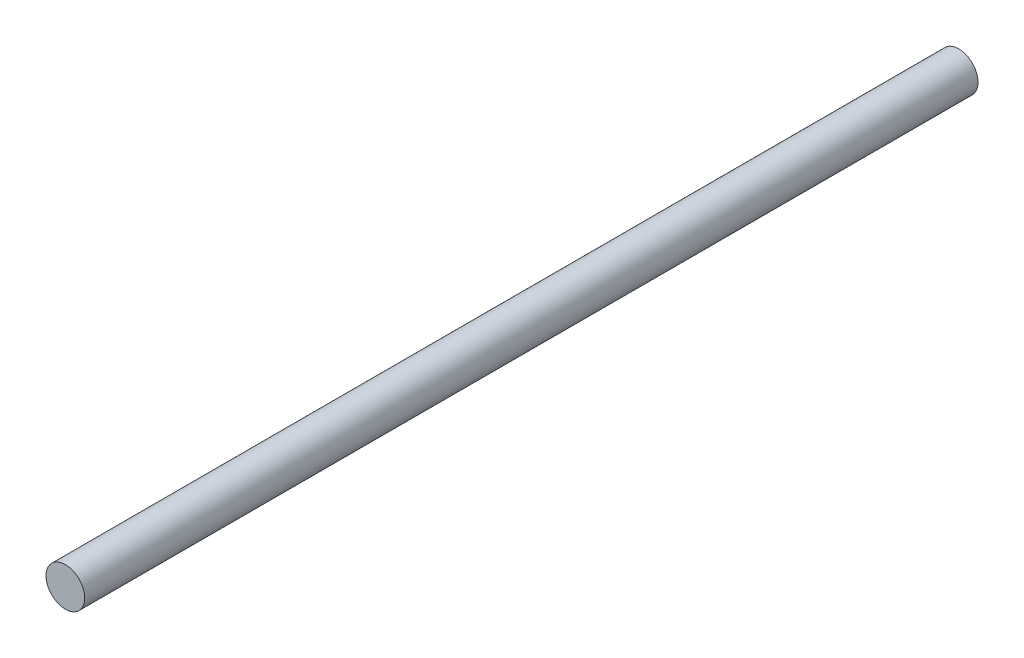
SolidWorks part; units mm, degrees
ref_plane "Front Plane" through (0, 0, 0) normal (0, 0, 1) x (1, 0, 0)
ref_plane "Top Plane" through (0, 0, 0) normal (0, 1, 0) x (1, 0, 0)
ref_plane "Right Plane" through (0, 0, 0) normal (1, 0, 0) x (0, 0, -1)
ref_plane "Plane1" through (0, 0, 0) normal (0, -1, 0) x (1, 0, 0)
sketch "Sketch1" plane through (0, 0, 0) normal (0, -1, 0) x (1, 0, 0)
  line L0 (3.9, 180) -> (0, 180)
  line L1 (0, 180) -> (0, 0)
  line L2 (0, 0) -> (3.9, 0)
  line L3 (3.9, 0) -> (3.9, 180)
  line L4 (0, 180) -> (0, 0) construction
revolve "Revolve1" add sketch "Sketch1" angle 360 about L4
